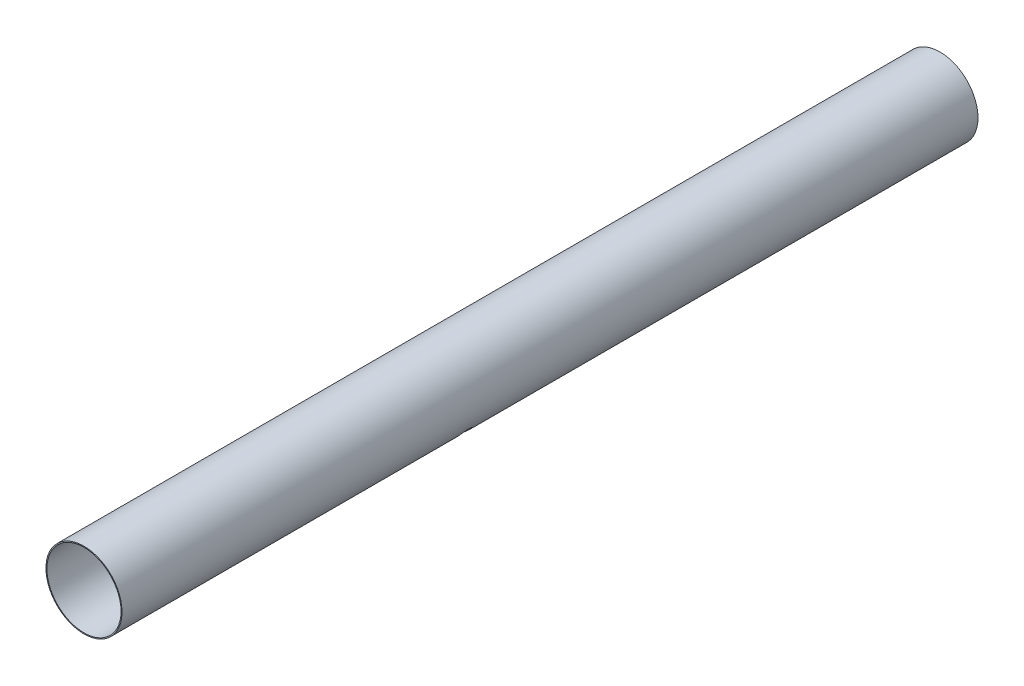
SolidWorks part; units mm, degrees
material "E-Glass Fiber"
ref_plane "Front" through (0, 0, 0) normal (0, 0, 1) x (1, 0, 0)
ref_plane "Top" through (0, 0, 0) normal (0, 1, 0) x (1, 0, 0)
ref_plane "Right" through (0, 0, 0) normal (1, 0, 0) x (0, 0, -1)
sketch "Sketch1" plane through (0, 0, 0) normal (0, 0, 1) x (1, 0, 0)
  circle A0 centre (0, 0) radius 78.2
  circle A1 centre (0, 0) radius 76.2
  dimension "D1" = 156.4
  dimension "D2" = 152.4
extrude "Boss-Extrude1" add sketch "Sketch1" along normal blind 1760
sketch "Sketch4" plane through (0, 0, 0) normal (0, 0, 1) x (1, 0, 0)
  line L0 (0, 0) -> (25.0476, -25.0476) construction
  line L1 (0, 0) -> (0, -24.8691) construction
  dimension "D1" = 45
ref_plane "Plane1" through (0, 0, 0) normal (0.7071, -0.7071, 0) x (0, 0, -1)
sketch "Sketch5" plane through (0, 0, 0) normal (0.7071, -0.7071, 0) x (0, 0, -1)
  line L0 (0, -78.2) -> (0, 78.2) construction
  circle A0 centre (-1034.89, 0) radius 15
  point P4 (0, 0)
  dimension "D1" = 30
  dimension "D2" = 1034.89
extrude "Cut-Extrude2" cut sketch "Sketch5" along normal through all
